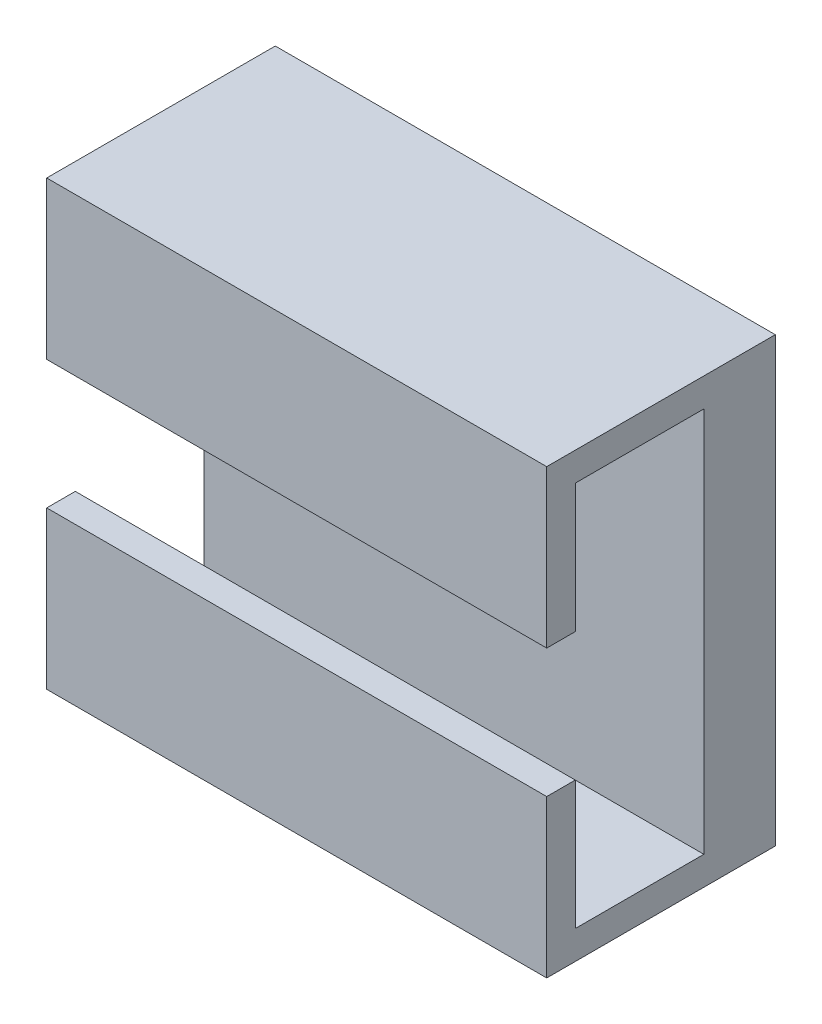
SolidWorks part; units mm, degrees
ref_plane "Plan de face" through (0, 0, 0) normal (0, 0, 1) x (1, 0, 0)
ref_plane "Plan de dessus" through (0, 0, 0) normal (0, 1, 0) x (1, 0, 0)
ref_plane "Plan de droite" through (0, 0, 0) normal (1, 0, 0) x (0, 0, -1)
sketch "Esquisse1" plane through (0, 0, 0) normal (0, 0, 1) x (1, 0, 0)
  line L0 (0, 0) -> (17.5, 15.5) construction
  line L1 (-17.5, -15.5) -> (17.5, -15.5)
  line L2 (-17.5, -15.5) -> (-17.5, 15.5)
  line L3 (-17.5, 15.5) -> (17.5, 15.5)
  line L4 (17.5, -15.5) -> (17.5, 15.5)
  line L5 (0, 0) -> (-17.5, -15.5) construction
  point P6 (-15.6659, -13.8653)
  point P7 (0, 0)
  point P10 (-17.5, -15.5)
  point P11 (-15.6279, -13.8418)
  point P13 (-15.3284, -13.5766)
  point P14 (0, 0)
  point P15 (-15.5884, -13.8069)
  point P16 (18.8017, 16.653)
  point P17 (7.0513, 6.2454)
  point P18 (21.4786, 19.0239)
  point P19 (0, 0)
  dimension "D1" = 35
  dimension "D2" = 31
extrude "Boss.-Extru.1" add sketch "Esquisse1" along normal blind 16
sketch "Esquisse2" plane through (-17.5, 0, 0) normal (-1, 0, 0) x (0, 0, 1)
  line L0 (5, 13.5) -> (5, -13.5)
  line L1 (5, -13.5) -> (14, -13.5)
  line L2 (14, -13.5) -> (14, -4.5)
  line L3 (14, -4.5) -> (16, -4.5)
  line L4 (16, 15.5) -> (16, -15.5) construction
  line L5 (16, -4.5) -> (16, 4.5)
  line L6 (16, 4.5) -> (14, 4.5)
  line L7 (14, 4.5) -> (14, 13.5)
  line L8 (14, 13.5) -> (5, 13.5)
  line L10 (16, -15.5) -> (0, -15.5) construction
  point P9 (16, 2.8455)
  dimension "D1" = 2
  dimension "D2" = 2
  dimension "D3" = 2
  dimension "D4" = 5
  dimension "D5" = 9
extrude "Enlèv. mat.-Extru.1" cut sketch "Esquisse2" against normal blind 35
sketch "Esquisse3" plane through (0, 0, 5) normal (0, 0, 1) x (1, 0, 0)
  circle A0 centre (0, 0) radius 1.75
  dimension "D1" = 3.5
extrude "Enlèv. mat.-Extru.2" cut sketch "Esquisse3" against normal up to vertex (5 mm away)
sketch "Esquisse4" plane through (0, 0, 5) normal (0, 0, 1) x (1, 0, 0)
  circle A0 centre (0, 0) radius 2.75
  dimension "D1" = 5.5
extrude "Enlèv. mat.-Extru.3" cut sketch "Esquisse4" against normal blind 3
